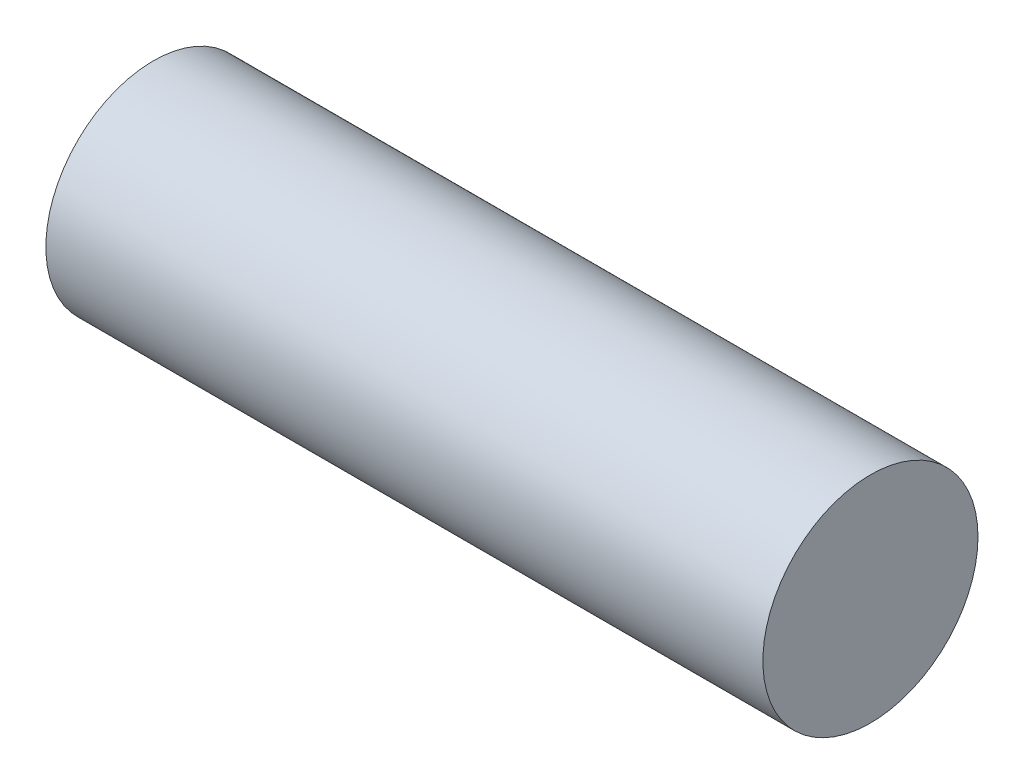
SolidWorks part; units mm, degrees
ref_plane "Front Plane" through (0, 0, 0) normal (0, 0, 1) x (1, 0, 0)
ref_plane "Top Plane" through (0, 0, 0) normal (0, 1, 0) x (1, 0, 0)
ref_plane "Right Plane" through (0, 0, 0) normal (1, 0, 0) x (0, 0, -1)
sketch "Sketch1" plane through (0, 0, 0) normal (1, 0, 0) x (0, 0, -1)
  circle A0 centre (0, 0) radius 4.7625
  dimension "D1" = 9.525
extrude "Boss-Extrude1" add sketch "Sketch1" along normal blind 31.75 contours A0
